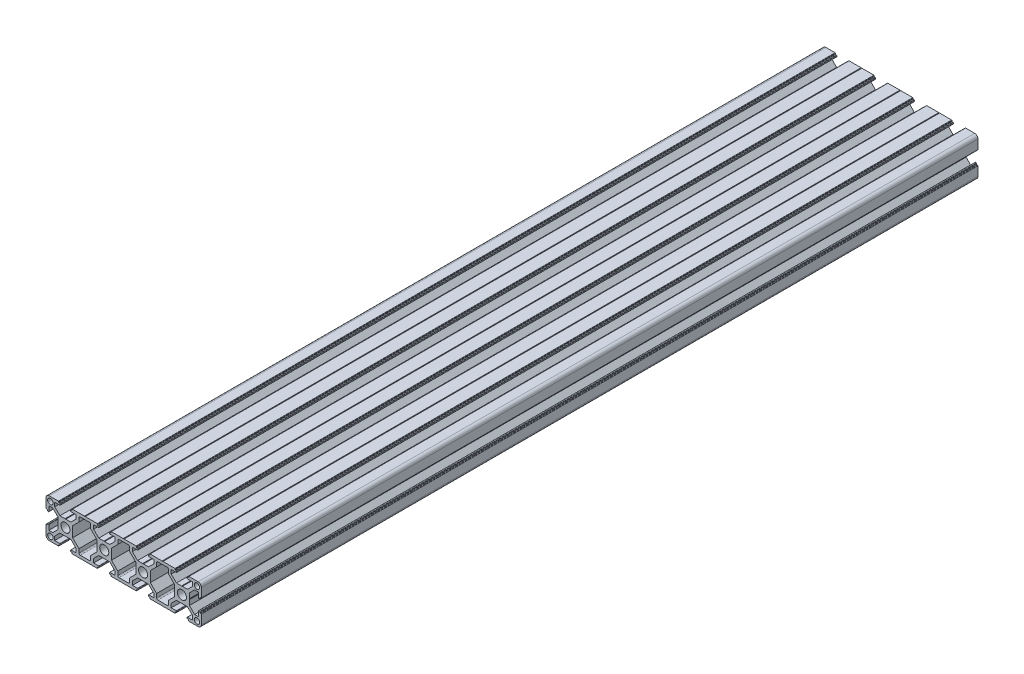
SolidWorks part; units mm, degrees
material "6063-T5"
ref_plane "Спереди" through (0, 0, 0) normal (0, 0, 1) x (1, 0, 0)
ref_plane "Сверху" through (0, 0, 0) normal (0, 1, 0) x (1, 0, 0)
ref_plane "Справа" through (0, 0, 0) normal (1, 0, 0) x (0, 0, -1)
sketch "Эскиз1" plane through (0, 600, 0) normal (0, 0, -1) x (1, 0, 0)
  line L0 (-25.45, 11.8) -> (-25.45, 8.8944)
  line L1 (-25.45, 8.8944) -> (-20.6, 4.0444)
  line L2 (-20.6, 4.0444) -> (-20.6, -4.0444)
  line L3 (-20.6, -4.0444) -> (-25.45, -8.8944)
  line L4 (-25.45, -8.8944) -> (-25.45, -11.8)
  line L5 (-26.45, -12.8) -> (-33.55, -12.8)
  line L6 (-34.55, -11.8) -> (-34.55, -8.8944)
  line L7 (-34.55, -8.8944) -> (-39.4, -4.0444)
  line L8 (-39.4, -4.0444) -> (-39.4, 4.0444)
  line L9 (-39.4, 4.0444) -> (-34.55, 8.8944)
  line L10 (-34.55, 8.8944) -> (-34.55, 11.8)
  line L11 (-33.55, 12.8) -> (-26.45, 12.8)
  line L12 (-4.55, -11.8) -> (-4.55, -8.8944)
  line L13 (-4.55, -8.8944) -> (-9.4, -4.0444)
  line L14 (-9.4, -4.0444) -> (-9.4, 4.0444)
  line L15 (-9.4, 4.0444) -> (-4.55, 8.8944)
  line L16 (-4.55, 8.8944) -> (-4.55, 11.8)
  line L17 (-3.55, 12.8) -> (3.55, 12.8)
  line L18 (4.55, 11.8) -> (4.55, 8.8944)
  line L19 (4.55, 8.8944) -> (9.4, 4.0444)
  line L20 (9.4, 4.0444) -> (9.4, -4.0444)
  line L21 (9.4, -4.0444) -> (4.55, -8.8944)
  line L22 (4.55, -8.8944) -> (4.55, -11.8)
  line L23 (3.55, -12.8) -> (-3.55, -12.8)
  line L24 (25.45, -8.8944) -> (20.6, -4.0444)
  line L25 (20.6, -4.0444) -> (20.6, 4.0444)
  line L26 (20.6, 4.0444) -> (25.45, 8.8944)
  line L27 (25.45, 8.8944) -> (25.45, 11.8)
  line L28 (26.45, 12.8) -> (33.55, 12.8)
  line L29 (34.55, 11.8) -> (34.55, 8.8944)
  line L30 (34.55, 8.8944) -> (39.4, 4.0444)
  line L31 (39.4, 4.0444) -> (39.4, -4.0444)
  line L32 (39.4, -4.0444) -> (34.55, -8.8944)
  line L33 (34.55, -8.8944) -> (34.55, -11.8)
  line L34 (33.55, -12.8) -> (26.45, -12.8)
  line L35 (25.45, -11.8) -> (25.45, -8.8944)
  line L36 (-57.5, -15) -> (-50.4, -15)
  line L37 (-50.2, -14.8) -> (-50.2, -14.2)
  line L38 (-50, -14) -> (-49.3, -14)
  line L39 (-49.1, -13.8) -> (-49.1, -13)
  line L40 (-49.3, -12.8) -> (-53.25, -12.8)
  line L41 (-53.25, -12.8) -> (-53.25, -9.8056)
  line L42 (-53.25, -9.8056) -> (-49.2444, -5.8)
  line L43 (-49.2444, -5.8) -> (-45.3377, -5.8)
  line L44 (-45.1815, -5.7452) -> (-45, -5.6)
  line L45 (-45, -5.6) -> (-44.8185, -5.7452)
  line L46 (-44.6623, -5.8) -> (-40.7556, -5.8)
  line L47 (-40.7556, -5.8) -> (-36.75, -9.8056)
  line L48 (-36.75, -9.8056) -> (-36.75, -12.8)
  line L49 (-36.75, -12.8) -> (-40.7, -12.8)
  line L50 (-40.9, -13) -> (-40.9, -13.8)
  line L51 (-40.7, -14) -> (-40, -14)
  line L52 (-39.8, -14.2) -> (-39.8, -14.8)
  line L53 (-39.6, -15) -> (-30.3377, -15)
  line L54 (-30.1815, -14.9452) -> (-30, -14.8)
  line L55 (-30, -14.8) -> (-29.8185, -14.9452)
  line L56 (-29.6623, -15) -> (-20.4, -15)
  line L57 (-20.2, -14.8) -> (-20.2, -14.2)
  line L58 (-20, -14) -> (-19.3, -14)
  line L59 (-19.1, -13.8) -> (-19.1, -13)
  line L60 (-19.3, -12.8) -> (-23.25, -12.8)
  line L61 (-23.25, -12.8) -> (-23.25, -9.8056)
  line L62 (-23.25, -9.8056) -> (-19.2444, -5.8)
  line L63 (-19.2444, -5.8) -> (-15.3377, -5.8)
  line L64 (-15.1815, -5.7452) -> (-15, -5.6)
  line L65 (-15, -5.6) -> (-14.8185, -5.7452)
  line L66 (-14.6623, -5.8) -> (-10.7556, -5.8)
  line L67 (-10.7556, -5.8) -> (-6.75, -9.8056)
  line L68 (-6.75, -9.8056) -> (-6.75, -12.8)
  line L69 (-6.75, -12.8) -> (-10.7, -12.8)
  line L70 (-10.9, -13) -> (-10.9, -13.8)
  line L71 (-10.7, -14) -> (-10, -14)
  line L72 (-9.8, -14.2) -> (-9.8, -14.8)
  line L73 (-9.6, -15) -> (-0.3377, -15)
  line L74 (-0.1815, -14.9452) -> (0, -14.8)
  line L75 (0, -14.8) -> (0.1815, -14.9452)
  line L76 (0.3377, -15) -> (9.6, -15)
  line L77 (9.8, -14.8) -> (9.8, -14.2)
  line L78 (10, -14) -> (10.7, -14)
  line L79 (10.9, -13.8) -> (10.9, -13)
  line L80 (10.7, -12.8) -> (6.75, -12.8)
  line L81 (6.75, -12.8) -> (6.75, -9.8056)
  line L82 (6.75, -9.8056) -> (10.7556, -5.8)
  line L83 (10.7556, -5.8) -> (14.6623, -5.8)
  line L84 (14.8185, -5.7452) -> (15, -5.6)
  line L85 (15, -5.6) -> (15.1815, -5.7452)
  line L86 (15.3377, -5.8) -> (19.2444, -5.8)
  line L87 (19.2444, -5.8) -> (23.25, -9.8056)
  line L88 (23.25, -9.8056) -> (23.25, -12.8)
  line L89 (23.25, -12.8) -> (19.3, -12.8)
  line L90 (19.1, -13) -> (19.1, -13.8)
  line L91 (19.3, -14) -> (20, -14)
  line L92 (20.2, -14.2) -> (20.2, -14.8)
  line L93 (20.4, -15) -> (29.6623, -15)
  line L94 (29.8185, -14.9452) -> (30, -14.8)
  line L95 (30, -14.8) -> (30.1815, -14.9452)
  line L96 (30.3377, -15) -> (39.6, -15)
  line L97 (39.8, -14.8) -> (39.8, -14.2)
  line L98 (40, -14) -> (40.7, -14)
  line L99 (40.9, -13.8) -> (40.9, -13)
  line L100 (40.7, -12.8) -> (36.75, -12.8)
  line L101 (36.75, -12.8) -> (36.75, -9.8056)
  line L102 (36.75, -9.8056) -> (40.7556, -5.8)
  line L103 (40.7556, -5.8) -> (44.6623, -5.8)
  line L104 (44.8185, -5.7452) -> (45, -5.6)
  line L105 (45, -5.6) -> (45.1815, -5.7452)
  line L106 (45.3377, -5.8) -> (49.2444, -5.8)
  line L107 (49.2444, -5.8) -> (53.25, -9.8056)
  line L108 (53.25, -9.8056) -> (53.25, -12.8)
  line L109 (53.25, -12.8) -> (49.3, -12.8)
  line L110 (49.1, -13) -> (49.1, -13.8)
  line L111 (49.3, -14) -> (50, -14)
  line L112 (50.2, -14.2) -> (50.2, -14.8)
  line L113 (50.4, -15) -> (57.5, -15)
  line L114 (60, -12.5) -> (60, -5.4)
  line L115 (59.8, -5.2) -> (59.2, -5.2)
  line L116 (59, -5) -> (59, -4.3)
  line L117 (58.8, -4.1) -> (58, -4.1)
  line L118 (57.8, -4.3) -> (57.8, -8.25)
  line L119 (57.8, -8.25) -> (54.8056, -8.25)
  line L120 (54.8056, -8.25) -> (50.8, -4.2444)
  line L121 (50.8, -4.2444) -> (50.8, -0.3377)
  line L122 (50.7452, -0.1815) -> (50.6, 0)
  line L123 (50.6, 0) -> (50.7452, 0.1815)
  line L124 (50.8, 0.3377) -> (50.8, 4.2444)
  line L125 (50.8, 4.2444) -> (54.8056, 8.25)
  line L126 (54.8056, 8.25) -> (57.8, 8.25)
  line L127 (57.8, 8.25) -> (57.8, 4.3)
  line L128 (58, 4.1) -> (58.8, 4.1)
  line L129 (59, 4.3) -> (59, 5)
  line L130 (59.2, 5.2) -> (59.8, 5.2)
  line L131 (60, 5.4) -> (60, 12.5)
  line L132 (57.5, 15) -> (50.4, 15)
  line L133 (50.2, 14.8) -> (50.2, 14.2)
  line L134 (50, 14) -> (49.3, 14)
  line L135 (49.1, 13.8) -> (49.1, 13)
  line L136 (49.3, 12.8) -> (53.25, 12.8)
  line L137 (53.25, 12.8) -> (53.25, 9.8056)
  line L138 (53.25, 9.8056) -> (49.2444, 5.8)
  line L139 (49.2444, 5.8) -> (45.3377, 5.8)
  line L140 (45.1815, 5.7452) -> (45, 5.6)
  line L141 (45, 5.6) -> (44.8185, 5.7452)
  line L142 (44.6623, 5.8) -> (40.7556, 5.8)
  line L143 (40.7556, 5.8) -> (36.75, 9.8056)
  line L144 (36.75, 9.8056) -> (36.75, 12.8)
  line L145 (36.75, 12.8) -> (40.7, 12.8)
  line L146 (40.9, 13) -> (40.9, 13.8)
  line L147 (40.7, 14) -> (40, 14)
  line L148 (39.8, 14.2) -> (39.8, 14.8)
  line L149 (39.6, 15) -> (30.3377, 15)
  line L150 (30.1815, 14.9452) -> (30, 14.8)
  line L151 (30, 14.8) -> (29.8185, 14.9452)
  line L152 (29.6623, 15) -> (20.4, 15)
  line L153 (20.2, 14.8) -> (20.2, 14.2)
  line L154 (20, 14) -> (19.3, 14)
  line L155 (19.1, 13.8) -> (19.1, 13)
  line L156 (19.3, 12.8) -> (23.25, 12.8)
  line L157 (23.25, 12.8) -> (23.25, 9.8056)
  line L158 (23.25, 9.8056) -> (19.2444, 5.8)
  line L159 (19.2444, 5.8) -> (15.3377, 5.8)
  line L160 (15.1815, 5.7452) -> (15, 5.6)
  line L161 (15, 5.6) -> (14.8185, 5.7452)
  line L162 (14.6623, 5.8) -> (10.7556, 5.8)
  line L163 (10.7556, 5.8) -> (6.75, 9.8056)
  line L164 (6.75, 9.8056) -> (6.75, 12.8)
  line L165 (6.75, 12.8) -> (10.7, 12.8)
  line L166 (10.9, 13) -> (10.9, 13.8)
  line L167 (10.7, 14) -> (10, 14)
  line L168 (9.8, 14.2) -> (9.8, 14.8)
  line L169 (9.6, 15) -> (0.3377, 15)
  line L170 (0.1815, 14.9452) -> (0, 14.8)
  line L171 (0, 14.8) -> (-0.1815, 14.9452)
  line L172 (-0.3377, 15) -> (-9.6, 15)
  line L173 (-9.8, 14.8) -> (-9.8, 14.2)
  line L174 (-10, 14) -> (-10.7, 14)
  line L175 (-10.9, 13.8) -> (-10.9, 13)
  line L176 (-10.7, 12.8) -> (-6.75, 12.8)
  line L177 (-6.75, 12.8) -> (-6.75, 9.8056)
  line L178 (-6.75, 9.8056) -> (-10.7556, 5.8)
  line L179 (-10.7556, 5.8) -> (-14.6623, 5.8)
  line L180 (-14.8185, 5.7452) -> (-15, 5.6)
  line L181 (-15, 5.6) -> (-15.1815, 5.7452)
  line L182 (-15.3377, 5.8) -> (-19.2444, 5.8)
  line L183 (-19.2444, 5.8) -> (-23.25, 9.8056)
  line L184 (-23.25, 9.8056) -> (-23.25, 12.8)
  line L185 (-23.25, 12.8) -> (-19.3, 12.8)
  line L186 (-19.1, 13) -> (-19.1, 13.8)
  line L187 (-19.3, 14) -> (-20, 14)
  line L188 (-20.2, 14.2) -> (-20.2, 14.8)
  line L189 (-20.4, 15) -> (-29.6623, 15)
  line L190 (-29.8185, 14.9452) -> (-30, 14.8)
  line L191 (-30, 14.8) -> (-30.1815, 14.9452)
  line L192 (-30.3377, 15) -> (-39.6, 15)
  line L193 (-39.8, 14.8) -> (-39.8, 14.2)
  line L194 (-40, 14) -> (-40.7, 14)
  line L195 (-40.9, 13.8) -> (-40.9, 13)
  line L196 (-40.7, 12.8) -> (-36.75, 12.8)
  line L197 (-36.75, 12.8) -> (-36.75, 9.8056)
  line L198 (-36.75, 9.8056) -> (-40.7556, 5.8)
  line L199 (-40.7556, 5.8) -> (-44.6623, 5.8)
  line L200 (-44.8185, 5.7452) -> (-45, 5.6)
  line L201 (-45, 5.6) -> (-45.1815, 5.7452)
  line L202 (-45.3377, 5.8) -> (-49.2444, 5.8)
  line L203 (-49.2444, 5.8) -> (-53.25, 9.8056)
  line L204 (-53.25, 9.8056) -> (-53.25, 12.8)
  line L205 (-53.25, 12.8) -> (-49.3, 12.8)
  line L206 (-49.1, 13) -> (-49.1, 13.8)
  line L207 (-49.3, 14) -> (-50, 14)
  line L208 (-50.2, 14.2) -> (-50.2, 14.8)
  line L209 (-50.4, 15) -> (-57.5, 15)
  line L210 (-60, 12.5) -> (-60, 5.4)
  line L211 (-59.8, 5.2) -> (-59.2, 5.2)
  line L212 (-59, 5) -> (-59, 4.3)
  line L213 (-58.8, 4.1) -> (-58, 4.1)
  line L214 (-57.8, 4.3) -> (-57.8, 8.25)
  line L215 (-57.8, 8.25) -> (-54.8056, 8.25)
  line L216 (-54.8056, 8.25) -> (-50.8, 4.2444)
  line L217 (-50.8, 4.2444) -> (-50.8, 0.3377)
  line L218 (-50.7452, 0.1815) -> (-50.6, 0)
  line L219 (-50.6, 0) -> (-50.7452, -0.1815)
  line L220 (-50.8, -0.3377) -> (-50.8, -4.2444)
  line L221 (-50.8, -4.2444) -> (-54.8056, -8.25)
  line L222 (-54.8056, -8.25) -> (-57.8, -8.25)
  line L223 (-57.8, -8.25) -> (-57.8, -4.3)
  line L224 (-58, -4.1) -> (-58.8, -4.1)
  line L225 (-59, -4.3) -> (-59, -5)
  line L226 (-59.2, -5.2) -> (-59.8, -5.2)
  line L227 (-60, -5.4) -> (-60, -12.5)
  circle A0 centre (-15, 0) radius 3.5
  circle A1 centre (-56.625, -11.625) radius 2.1
  circle A2 centre (-56.625, 11.625) radius 2.1
  circle A3 centre (56.625, -11.625) radius 2.1
  circle A4 centre (56.625, 11.625) radius 2.1
  circle A5 centre (-45, 0) radius 3.5
  circle A6 centre (15, 0) radius 3.5
  circle A7 centre (45, 0) radius 3.5
  arc A8 (-25.45, -11.8) -> (-26.45, -12.8) centre (-26.45, -11.8) cw
  arc A9 (-33.55, -12.8) -> (-34.55, -11.8) centre (-33.55, -11.8) cw
  arc A10 (-34.55, 11.8) -> (-33.55, 12.8) centre (-33.55, 11.8) cw
  arc A11 (-26.45, 12.8) -> (-25.45, 11.8) centre (-26.45, 11.8) cw
  arc A12 (-3.55, -12.8) -> (-4.55, -11.8) centre (-3.55, -11.8) cw
  arc A13 (-4.55, 11.8) -> (-3.55, 12.8) centre (-3.55, 11.8) cw
  arc A14 (3.55, 12.8) -> (4.55, 11.8) centre (3.55, 11.8) cw
  arc A15 (4.55, -11.8) -> (3.55, -12.8) centre (3.55, -11.8) cw
  arc A16 (25.45, 11.8) -> (26.45, 12.8) centre (26.45, 11.8) cw
  arc A17 (33.55, 12.8) -> (34.55, 11.8) centre (33.55, 11.8) cw
  arc A18 (34.55, -11.8) -> (33.55, -12.8) centre (33.55, -11.8) cw
  arc A19 (26.45, -12.8) -> (25.45, -11.8) centre (26.45, -11.8) cw
  arc A20 (-60, -12.5) -> (-57.5, -15) centre (-57.5, -12.5) ccw
  arc A21 (-50.4, -15) -> (-50.2, -14.8) centre (-50.4, -14.8) ccw
  arc A22 (-50.2, -14.2) -> (-50, -14) centre (-50, -14.2) cw
  arc A23 (-49.3, -14) -> (-49.1, -13.8) centre (-49.3, -13.8) ccw
  arc A24 (-49.1, -13) -> (-49.3, -12.8) centre (-49.3, -13) ccw
  arc A25 (-45.3377, -5.8) -> (-45.1815, -5.7452) centre (-45.3377, -5.55) ccw
  arc A26 (-44.8185, -5.7452) -> (-44.6623, -5.8) centre (-44.6623, -5.55) ccw
  arc A27 (-40.7, -12.8) -> (-40.9, -13) centre (-40.7, -13) ccw
  arc A28 (-40.9, -13.8) -> (-40.7, -14) centre (-40.7, -13.8) ccw
  arc A29 (-40, -14) -> (-39.8, -14.2) centre (-40, -14.2) cw
  arc A30 (-39.8, -14.8) -> (-39.6, -15) centre (-39.6, -14.8) ccw
  arc A31 (-30.3377, -15) -> (-30.1815, -14.9452) centre (-30.3377, -14.75) ccw
  arc A32 (-29.8185, -14.9452) -> (-29.6623, -15) centre (-29.6623, -14.75) ccw
  arc A33 (-20.4, -15) -> (-20.2, -14.8) centre (-20.4, -14.8) ccw
  arc A34 (-20.2, -14.2) -> (-20, -14) centre (-20, -14.2) cw
  arc A35 (-19.3, -14) -> (-19.1, -13.8) centre (-19.3, -13.8) ccw
  arc A36 (-19.1, -13) -> (-19.3, -12.8) centre (-19.3, -13) ccw
  arc A37 (-15.3377, -5.8) -> (-15.1815, -5.7452) centre (-15.3377, -5.55) ccw
  arc A38 (-14.8185, -5.7452) -> (-14.6623, -5.8) centre (-14.6623, -5.55) ccw
  arc A39 (-10.7, -12.8) -> (-10.9, -13) centre (-10.7, -13) ccw
  arc A40 (-10.9, -13.8) -> (-10.7, -14) centre (-10.7, -13.8) ccw
  arc A41 (-10, -14) -> (-9.8, -14.2) centre (-10, -14.2) cw
  arc A42 (-9.8, -14.8) -> (-9.6, -15) centre (-9.6, -14.8) ccw
  arc A43 (-0.3377, -15) -> (-0.1815, -14.9452) centre (-0.3377, -14.75) ccw
  arc A44 (0.1815, -14.9452) -> (0.3377, -15) centre (0.3377, -14.75) ccw
  arc A45 (9.6, -15) -> (9.8, -14.8) centre (9.6, -14.8) ccw
  arc A46 (9.8, -14.2) -> (10, -14) centre (10, -14.2) cw
  arc A47 (10.7, -14) -> (10.9, -13.8) centre (10.7, -13.8) ccw
  arc A48 (10.9, -13) -> (10.7, -12.8) centre (10.7, -13) ccw
  arc A49 (14.6623, -5.8) -> (14.8185, -5.7452) centre (14.6623, -5.55) ccw
  arc A50 (15.1815, -5.7452) -> (15.3377, -5.8) centre (15.3377, -5.55) ccw
  arc A51 (19.3, -12.8) -> (19.1, -13) centre (19.3, -13) ccw
  arc A52 (19.1, -13.8) -> (19.3, -14) centre (19.3, -13.8) ccw
  arc A53 (20, -14) -> (20.2, -14.2) centre (20, -14.2) cw
  arc A54 (20.2, -14.8) -> (20.4, -15) centre (20.4, -14.8) ccw
  arc A55 (29.6623, -15) -> (29.8185, -14.9452) centre (29.6623, -14.75) ccw
  arc A56 (30.1815, -14.9452) -> (30.3377, -15) centre (30.3377, -14.75) ccw
  arc A57 (39.6, -15) -> (39.8, -14.8) centre (39.6, -14.8) ccw
  arc A58 (39.8, -14.2) -> (40, -14) centre (40, -14.2) cw
  arc A59 (40.7, -14) -> (40.9, -13.8) centre (40.7, -13.8) ccw
  arc A60 (40.9, -13) -> (40.7, -12.8) centre (40.7, -13) ccw
  arc A61 (44.6623, -5.8) -> (44.8185, -5.7452) centre (44.6623, -5.55) ccw
  arc A62 (45.1815, -5.7452) -> (45.3377, -5.8) centre (45.3377, -5.55) ccw
  arc A63 (49.3, -12.8) -> (49.1, -13) centre (49.3, -13) ccw
  arc A64 (49.1, -13.8) -> (49.3, -14) centre (49.3, -13.8) ccw
  arc A65 (50, -14) -> (50.2, -14.2) centre (50, -14.2) cw
  arc A66 (50.2, -14.8) -> (50.4, -15) centre (50.4, -14.8) ccw
  arc A67 (57.5, -15) -> (60, -12.5) centre (57.5, -12.5) ccw
  arc A68 (60, -5.4) -> (59.8, -5.2) centre (59.8, -5.4) ccw
  arc A69 (59.2, -5.2) -> (59, -5) centre (59.2, -5) cw
  arc A70 (59, -4.3) -> (58.8, -4.1) centre (58.8, -4.3) ccw
  arc A71 (58, -4.1) -> (57.8, -4.3) centre (58, -4.3) ccw
  arc A72 (50.8, -0.3377) -> (50.7452, -0.1815) centre (50.55, -0.3377) ccw
  arc A73 (50.7452, 0.1815) -> (50.8, 0.3377) centre (50.55, 0.3377) ccw
  arc A74 (57.8, 4.3) -> (58, 4.1) centre (58, 4.3) ccw
  arc A75 (58.8, 4.1) -> (59, 4.3) centre (58.8, 4.3) ccw
  arc A76 (59, 5) -> (59.2, 5.2) centre (59.2, 5) cw
  arc A77 (59.8, 5.2) -> (60, 5.4) centre (59.8, 5.4) ccw
  arc A78 (60, 12.5) -> (57.5, 15) centre (57.5, 12.5) ccw
  arc A79 (50.4, 15) -> (50.2, 14.8) centre (50.4, 14.8) ccw
  arc A80 (50.2, 14.2) -> (50, 14) centre (50, 14.2) cw
  arc A81 (49.3, 14) -> (49.1, 13.8) centre (49.3, 13.8) ccw
  arc A82 (49.1, 13) -> (49.3, 12.8) centre (49.3, 13) ccw
  arc A83 (45.3377, 5.8) -> (45.1815, 5.7452) centre (45.3377, 5.55) ccw
  arc A84 (44.8185, 5.7452) -> (44.6623, 5.8) centre (44.6623, 5.55) ccw
  arc A85 (40.7, 12.8) -> (40.9, 13) centre (40.7, 13) ccw
  arc A86 (40.9, 13.8) -> (40.7, 14) centre (40.7, 13.8) ccw
  arc A87 (40, 14) -> (39.8, 14.2) centre (40, 14.2) cw
  arc A88 (39.8, 14.8) -> (39.6, 15) centre (39.6, 14.8) ccw
  arc A89 (30.3377, 15) -> (30.1815, 14.9452) centre (30.3377, 14.75) ccw
  arc A90 (29.8185, 14.9452) -> (29.6623, 15) centre (29.6623, 14.75) ccw
  arc A91 (20.4, 15) -> (20.2, 14.8) centre (20.4, 14.8) ccw
  arc A92 (20.2, 14.2) -> (20, 14) centre (20, 14.2) cw
  arc A93 (19.3, 14) -> (19.1, 13.8) centre (19.3, 13.8) ccw
  arc A94 (19.1, 13) -> (19.3, 12.8) centre (19.3, 13) ccw
  arc A95 (15.3377, 5.8) -> (15.1815, 5.7452) centre (15.3377, 5.55) ccw
  arc A96 (14.8185, 5.7452) -> (14.6623, 5.8) centre (14.6623, 5.55) ccw
  arc A97 (10.7, 12.8) -> (10.9, 13) centre (10.7, 13) ccw
  arc A98 (10.9, 13.8) -> (10.7, 14) centre (10.7, 13.8) ccw
  arc A99 (10, 14) -> (9.8, 14.2) centre (10, 14.2) cw
  arc A100 (9.8, 14.8) -> (9.6, 15) centre (9.6, 14.8) ccw
  arc A101 (0.3377, 15) -> (0.1815, 14.9452) centre (0.3377, 14.75) ccw
  arc A102 (-0.1815, 14.9452) -> (-0.3377, 15) centre (-0.3377, 14.75) ccw
  arc A103 (-9.6, 15) -> (-9.8, 14.8) centre (-9.6, 14.8) ccw
  arc A104 (-9.8, 14.2) -> (-10, 14) centre (-10, 14.2) cw
  arc A105 (-10.7, 14) -> (-10.9, 13.8) centre (-10.7, 13.8) ccw
  arc A106 (-10.9, 13) -> (-10.7, 12.8) centre (-10.7, 13) ccw
  arc A107 (-14.6623, 5.8) -> (-14.8185, 5.7452) centre (-14.6623, 5.55) ccw
  arc A108 (-15.1815, 5.7452) -> (-15.3377, 5.8) centre (-15.3377, 5.55) ccw
  arc A109 (-19.3, 12.8) -> (-19.1, 13) centre (-19.3, 13) ccw
  arc A110 (-19.1, 13.8) -> (-19.3, 14) centre (-19.3, 13.8) ccw
  arc A111 (-20, 14) -> (-20.2, 14.2) centre (-20, 14.2) cw
  arc A112 (-20.2, 14.8) -> (-20.4, 15) centre (-20.4, 14.8) ccw
  arc A113 (-29.6623, 15) -> (-29.8185, 14.9452) centre (-29.6623, 14.75) ccw
  arc A114 (-30.1815, 14.9452) -> (-30.3377, 15) centre (-30.3377, 14.75) ccw
  arc A115 (-39.6, 15) -> (-39.8, 14.8) centre (-39.6, 14.8) ccw
  arc A116 (-39.8, 14.2) -> (-40, 14) centre (-40, 14.2) cw
  arc A117 (-40.7, 14) -> (-40.9, 13.8) centre (-40.7, 13.8) ccw
  arc A118 (-40.9, 13) -> (-40.7, 12.8) centre (-40.7, 13) ccw
  arc A119 (-44.6623, 5.8) -> (-44.8185, 5.7452) centre (-44.6623, 5.55) ccw
  arc A120 (-45.1815, 5.7452) -> (-45.3377, 5.8) centre (-45.3377, 5.55) ccw
  arc A121 (-49.3, 12.8) -> (-49.1, 13) centre (-49.3, 13) ccw
  arc A122 (-49.1, 13.8) -> (-49.3, 14) centre (-49.3, 13.8) ccw
  arc A123 (-50, 14) -> (-50.2, 14.2) centre (-50, 14.2) cw
  arc A124 (-50.2, 14.8) -> (-50.4, 15) centre (-50.4, 14.8) ccw
  arc A125 (-57.5, 15) -> (-60, 12.5) centre (-57.5, 12.5) ccw
  arc A126 (-60, 5.4) -> (-59.8, 5.2) centre (-59.8, 5.4) ccw
  arc A127 (-59.2, 5.2) -> (-59, 5) centre (-59.2, 5) cw
  arc A128 (-59, 4.3) -> (-58.8, 4.1) centre (-58.8, 4.3) ccw
  arc A129 (-58, 4.1) -> (-57.8, 4.3) centre (-58, 4.3) ccw
  arc A130 (-50.8, 0.3377) -> (-50.7452, 0.1815) centre (-50.55, 0.3377) ccw
  arc A131 (-50.7452, -0.1815) -> (-50.8, -0.3377) centre (-50.55, -0.3377) ccw
  arc A132 (-57.8, -4.3) -> (-58, -4.1) centre (-58, -4.3) ccw
  arc A133 (-58.8, -4.1) -> (-59, -4.3) centre (-58.8, -4.3) ccw
  arc A134 (-59, -5) -> (-59.2, -5.2) centre (-59.2, -5) cw
  arc A135 (-59.8, -5.2) -> (-60, -5.4) centre (-59.8, -5.4) ccw
extrude "Бобышка-Вытянуть1" add sketch "Эскиз1" against normal blind 600
